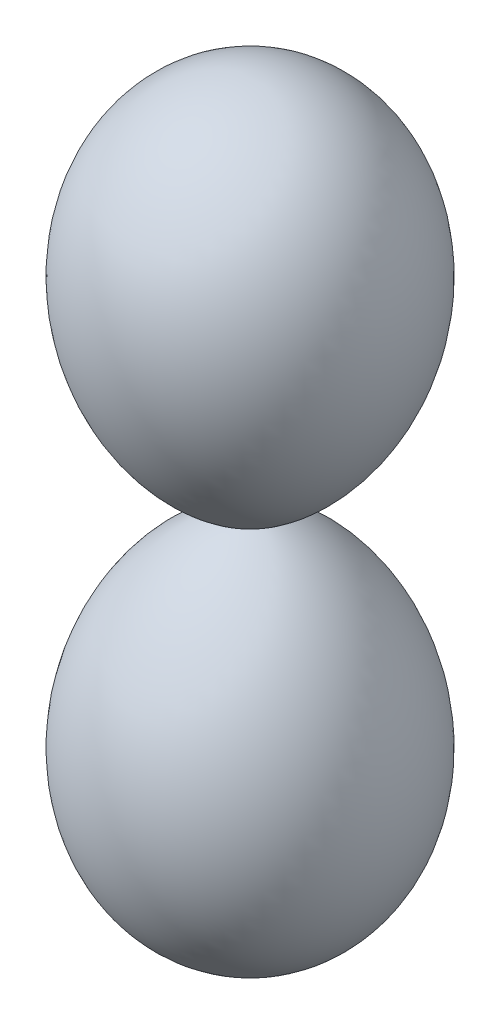
SolidWorks part; units mm, degrees
ref_plane "Front Plane" through (0, 0, 0) normal (0, 0, 1) x (1, 0, 0)
ref_plane "Top Plane" through (0, 0, 0) normal (0, 1, 0) x (1, 0, 0)
ref_plane "Right Plane" through (0, 0, 0) normal (1, 0, 0) x (0, 0, -1)
sketch "Sketch" plane through (0, 0, 0) normal (0, 0, 1) x (1, 0, 0)
  line L0 (0, 238.7324) -> (0, -238.7324) construction
  line L1 (0, -238.7324) -> (0, 238.7324)
  spline S0 degree 4 poles (-59.1636, -213.6977) (-57.9875, -214.8514) (-55.5824, -217.1048) (-51.819, -220.315) (-46.5064, -224.2237) (-40.9191, -227.7295) (-35.082, -230.8017) (-29.7811, -233.0857) (-25.5084, -234.6008) (-22.3543, -235.5556) (-20.3679, -236.099) (-18.7702, -236.5014) (-17.1647, -236.8713) (-15.552, -237.2084) (-13.9328, -237.5125) (-12.3075, -237.7833) (-10.8811, -237.991) (-9.6552, -238.1481) (-8.428, -238.2883) (-7.1976, -238.4116) (-5.7627, -238.5307) (-4.1152, -238.633) (-2.6802, -238.6926) (-1.538, -238.72) (-0.7367, -238.7299) (-0.0437, -238.733) (0.2995, -238.7322) (1.3341, -238.7258) (1.7348, -238.7113) (2.7843, -238.6895) (3.3274, -238.6605) (4.2336, -238.6243) (4.8993, -238.5809) (5.7104, -238.5302) (6.4396, -238.4723) (7.2099, -238.4072) (7.9602, -238.3349) (8.9068, -238.2355) (10.0369, -238.1019) (11.3551, -237.9251) (12.8562, -237.6946) (14.3534, -237.4358) (15.845, -237.1487) (17.3311, -236.8335) (18.8109, -236.4905) (20.2842, -236.1198) (21.7502, -235.7217) (23.2085, -235.2963) (24.6587, -234.844) (27.1816, -234.0056) (30.0285, -232.9416) (33.8776, -231.3131) (38.6437, -228.951) (43.2636, -226.3111) (48.3219, -222.9361) (53.1406, -219.2275) (57.7048, -215.2101) (62.0021, -210.9087) (66.023, -206.3482) (69.7602, -201.5527) (73.2083, -196.5456) (76.364, -191.3494) (79.2253, -185.9856) (81.7916, -180.4748) (84.0633, -174.8364) (86.0418, -169.0886) (87.7291, -163.2489) (89.128, -157.3335) (90.2414, -151.3579) (91.073, -145.3368) (91.6265, -139.2838) (91.9755, -131.6941) (91.8542, -122.5737) (90.9432, -111.9665) (88.8806, -99.9761) (85.8303, -88.1987) (81.8247, -76.7112) (76.8952, -65.5888) (71.0717, -54.9071) (64.3826, -44.7443) (56.8548, -35.1853) (48.5135, -26.325) (39.3827, -18.2777) (29.5582, -11.2399) (20.3305, -6.0887) (12.7444, -2.9093) (7.1234, -1.1975) (3.8925, -0.4721) (2.0734, -0.1745) (0.8971, -0.0493) (0.3849, -0.015) (0.2375, -0.0072) (0.1285, -0.0027) (0.0595, -0.0008) (0.0216, -0.0002) (0.006, 0) (0.0023, 0) (0.0006, 0) (0.0003, 0) (0.0021, 0) (0.0059, 0) (0.0113, 0.0001) (0.0305, 0.0003) (0.0713, 0.0011) (0.1415, 0.0032) (0.2478, 0.0077) (0.3873, 0.0152) (0.7653, 0.0403) (1.7632, 0.1367) (3.3639, 0.3769) (6.3647, 1.0007) (11.5988, 2.5118) (18.8362, 5.3918) (27.7742, 10.1527) (37.3635, 16.7121) (46.5021, 24.427) (54.8834, 32.9552) (62.4851, 42.1832) (69.2833, 52.0169) (75.2532, 62.3739) (80.3682, 73.1784) (84.6003, 84.3582) (87.9203, 95.8421) (90.2975, 107.5579) (91.7005, 119.4303) (92.0971, 131.3795) (91.4552, 143.319) (89.9579, 153.6745) (87.9883, 162.4193) (85.8822, 169.5823) (83.9161, 175.2225) (81.6667, 180.756) (79.1328, 186.1654) (76.3141, 191.432) (73.2112, 196.5365) (69.8258, 201.4586) (66.1614, 206.1767) (62.2228, 210.6688) (58.0168, 214.9118) (53.5525, 218.8825) (49.4301, 222.0977) (45.751, 224.6539) (42.5933, 226.6436) (40.0143, 228.1483) (37.3849, 229.5632) (34.7078, 230.8856) (31.9857, 232.1129) (29.2218, 233.2427) (26.419, 234.2727) (23.5811, 235.2006) (20.7107, 236.0245) (18.1752, 236.6528) (15.9852, 237.1243) (14.1535, 237.472) (12.6792, 237.7228) (11.2086, 237.9463) (9.7192, 238.1422) (8.3897, 238.2949) (7.1537, 238.4122) (6.123, 238.501) (5.1039, 238.5673) (4.3417, 238.6226) (3.1586, 238.6614) (3.1504, 238.6877) (1.5434, 238.705) (1.8287, 238.716) (1.1243, 238.7264) (0.2091, 238.7331) (-0.1917, 238.7334) (-1.3682, 238.7246) (-1.9645, 238.7075) (-2.9481, 238.682) (-3.6616, 238.6479) (-4.5564, 238.6053) (-5.3329, 238.5542) (-6.1822, 238.4946) (-6.9871, 238.4265) (-7.816, 238.3499) (-8.631, 238.2649) (-9.6561, 238.1481) (-10.8805, 237.991) (-12.3079, 237.7833) (-13.9326, 237.5125) (-15.5521, 237.2084) (-17.1646, 236.8713) (-18.7702, 236.5014) (-20.3678, 236.099) (-21.9571, 235.6642) (-23.5371, 235.1975) (-25.1075, 234.6991) (-27.4476, 233.9045) (-30.917, 232.5963) (-35.4468, 230.6097) (-40.9191, 227.7295) (-46.5064, 224.2237) (-51.819, 220.315) (-55.5824, 217.1048) (-57.9875, 214.8514) (-59.1636, 213.6977) knots 0 0 0 0 0 0.008333 0.016667 0.025 0.033333 0.041667 0.05 0.054167 0.05625 0.058333 0.060416 0.0625 0.064583 0.066666 0.06875 0.070833 0.071875 0.072916 0.075 0.077083 0.079166 0.08125 0.082291 0.082812 0.083333 0.084294 0.085254 0.086214 0.087175 0.088135 0.089096 0.090056 0.091017 0.091977 0.092938 0.093898 0.094859 0.09678 0.0987 0.100621 0.102542 0.104463 0.106384 0.108305 0.110226 0.112147 0.114068 0.115989 0.11791 0.125593 0.129435 0.137119 0.144803 0.152486 0.16017 0.167854 0.175537 0.183221 0.190905 0.198589 0.206272 0.213956 0.22164 0.229324 0.237007 0.244691 0.252375 0.260058 0.267742 0.275426 0.28311 0.298477 0.313845 0.329212 0.34458 0.359947 0.375315 0.390682 0.40605 0.421417 0.436784 0.452152 0.467519 0.482432 0.490114 0.493662 0.497209 0.499172 0.499432 0.499643 0.499805 0.499919 0.499983 0.499992 0.499996 0.499999 0.5 0.500001 0.500004 0.500008 0.500015 0.50003 0.500101 0.500215 0.50037 0.500568 0.500808 0.502131 0.50544 0.50875 0.516302 0.529657 0.544757 0.559858 0.574959 0.590059 0.605159 0.62026 0.635361 0.650461 0.665562 0.680662 0.695763 0.710863 0.725964 0.741064 0.756165 0.763715 0.771265 0.778816 0.786366 0.793916 0.801467 0.809017 0.816567 0.824117 0.831668 0.839218 0.846768 0.854318 0.858093 0.861869 0.865644 0.869419 0.873194 0.876969 0.880744 0.884519 0.888294 0.89207 0.895845 0.897732 0.89962 0.901507 0.903395 0.905282 0.90717 0.908357 0.909544 0.910731 0.911918 0.913106 0.913699 0.914293 0.914886 0.91548 0.916667 0.917709 0.91875 0.919792 0.920834 0.921875 0.922917 0.923959 0.925 0.926042 0.927084 0.928125 0.929167 0.93125 0.933334 0.935417 0.9375 0.939584 0.941667 0.94375 0.945833 0.947917 0.95 0.952083 0.958333 0.966667 0.975 0.983333 0.991667 1 1 1 1 1 construction
  spline S1 degree 4 poles (0, -238.7324) (0.1582, -238.7324) (0.4579, -238.7312) (1.3341, -238.7258) (1.7348, -238.7113) (2.7843, -238.6895) (3.3274, -238.6605) (4.2336, -238.6243) (4.8993, -238.5809) (5.7104, -238.5302) (6.4396, -238.4723) (7.2099, -238.4072) (7.9602, -238.3349) (8.9068, -238.2355) (10.0369, -238.1019) (11.3551, -237.9251) (12.8562, -237.6946) (14.3534, -237.4358) (15.845, -237.1487) (17.3311, -236.8335) (18.8109, -236.4905) (20.2842, -236.1198) (21.7502, -235.7217) (23.2085, -235.2963) (24.6587, -234.844) (27.1816, -234.0056) (30.0285, -232.9416) (33.8776, -231.3131) (38.6437, -228.951) (43.2636, -226.3111) (48.3219, -222.9361) (53.1406, -219.2275) (57.7048, -215.2101) (62.0021, -210.9087) (66.023, -206.3482) (69.7602, -201.5527) (73.2083, -196.5456) (76.364, -191.3494) (79.2253, -185.9856) (81.7916, -180.4748) (84.0633, -174.8364) (86.0418, -169.0886) (87.7291, -163.2489) (89.128, -157.3335) (90.2414, -151.3579) (91.073, -145.3368) (91.6265, -139.2838) (91.9755, -131.6941) (91.8542, -122.5737) (90.9432, -111.9665) (88.8806, -99.9761) (85.8303, -88.1987) (81.8247, -76.7112) (76.8952, -65.5888) (71.0717, -54.9071) (64.3826, -44.7443) (56.8548, -35.1853) (48.5135, -26.325) (39.3827, -18.2777) (29.5582, -11.2399) (20.3305, -6.0887) (12.7444, -2.9093) (7.1234, -1.1975) (3.8925, -0.4721) (2.0734, -0.1745) (0.8971, -0.0493) (0.3849, -0.015) (0.2375, -0.0072) (0.1285, -0.0027) (0.0595, -0.0008) (0.0216, -0.0002) (0.006, 0) (0.0023, 0) (0.0006, 0) (0.0003, 0) (0.0021, 0) (0.0059, 0) (0.0113, 0.0001) (0.0305, 0.0003) (0.0713, 0.0011) (0.1415, 0.0032) (0.2478, 0.0077) (0.3873, 0.0152) (0.7653, 0.0403) (1.7632, 0.1367) (3.3639, 0.3769) (6.3647, 1.0007) (11.5988, 2.5118) (18.8362, 5.3918) (27.7742, 10.1527) (37.3635, 16.7121) (46.5021, 24.427) (54.8834, 32.9552) (62.4851, 42.1832) (69.2833, 52.0169) (75.2532, 62.3739) (80.3682, 73.1784) (84.6003, 84.3582) (87.9203, 95.8421) (90.2975, 107.5579) (91.7005, 119.4303) (92.0971, 131.3795) (91.4552, 143.319) (89.9579, 153.6745) (87.9883, 162.4193) (85.8822, 169.5823) (83.9161, 175.2225) (81.6667, 180.756) (79.1328, 186.1654) (76.3141, 191.432) (73.2112, 196.5365) (69.8258, 201.4586) (66.1614, 206.1767) (62.2228, 210.6688) (58.0168, 214.9118) (53.5525, 218.8825) (49.4301, 222.0977) (45.751, 224.6539) (42.5933, 226.6436) (40.0143, 228.1483) (37.3849, 229.5632) (34.7078, 230.8856) (31.9857, 232.1129) (29.2218, 233.2427) (26.419, 234.2727) (23.5811, 235.2006) (20.7107, 236.0245) (18.1752, 236.6528) (15.9852, 237.1243) (14.1535, 237.472) (12.6792, 237.7228) (11.2086, 237.9463) (9.7192, 238.1422) (8.3897, 238.2949) (7.1537, 238.4122) (6.123, 238.501) (5.1039, 238.5673) (4.3417, 238.6226) (3.1586, 238.6614) (3.1504, 238.6877) (1.5434, 238.705) (1.8287, 238.716) (1.1243, 238.7264) (0.4882, 238.731) (0.1956, 238.7324) (0, 238.7324) knots 0.083333 0.083333 0.083333 0.083333 0.083333 0.084294 0.085254 0.086214 0.087175 0.088135 0.089096 0.090056 0.091017 0.091977 0.092938 0.093898 0.094859 0.09678 0.0987 0.100621 0.102542 0.104463 0.106384 0.108305 0.110226 0.112147 0.114068 0.115989 0.11791 0.125593 0.129435 0.137119 0.144803 0.152486 0.16017 0.167854 0.175537 0.183221 0.190905 0.198589 0.206272 0.213956 0.22164 0.229324 0.237007 0.244691 0.252375 0.260058 0.267742 0.275426 0.28311 0.298477 0.313845 0.329212 0.34458 0.359947 0.375315 0.390682 0.40605 0.421417 0.436784 0.452152 0.467519 0.482432 0.490114 0.493662 0.497209 0.499172 0.499432 0.499643 0.499805 0.499919 0.499983 0.499992 0.499996 0.499999 0.5 0.500001 0.500004 0.500008 0.500015 0.50003 0.500101 0.500215 0.50037 0.500568 0.500808 0.502131 0.50544 0.50875 0.516302 0.529657 0.544757 0.559858 0.574959 0.590059 0.605159 0.62026 0.635361 0.650461 0.665562 0.680662 0.695763 0.710863 0.725964 0.741064 0.756165 0.763715 0.771265 0.778816 0.786366 0.793916 0.801467 0.809017 0.816567 0.824117 0.831668 0.839218 0.846768 0.854318 0.858093 0.861869 0.865644 0.869419 0.873194 0.876969 0.880744 0.884519 0.888294 0.89207 0.895845 0.897732 0.89962 0.901507 0.903395 0.905282 0.90717 0.908357 0.909544 0.910731 0.911918 0.913106 0.913699 0.914293 0.914886 0.91548 0.916667 0.916667 0.916667 0.916667 0.916667
revolve "Revolve" add sketch "Sketch" angle 360 about L0
